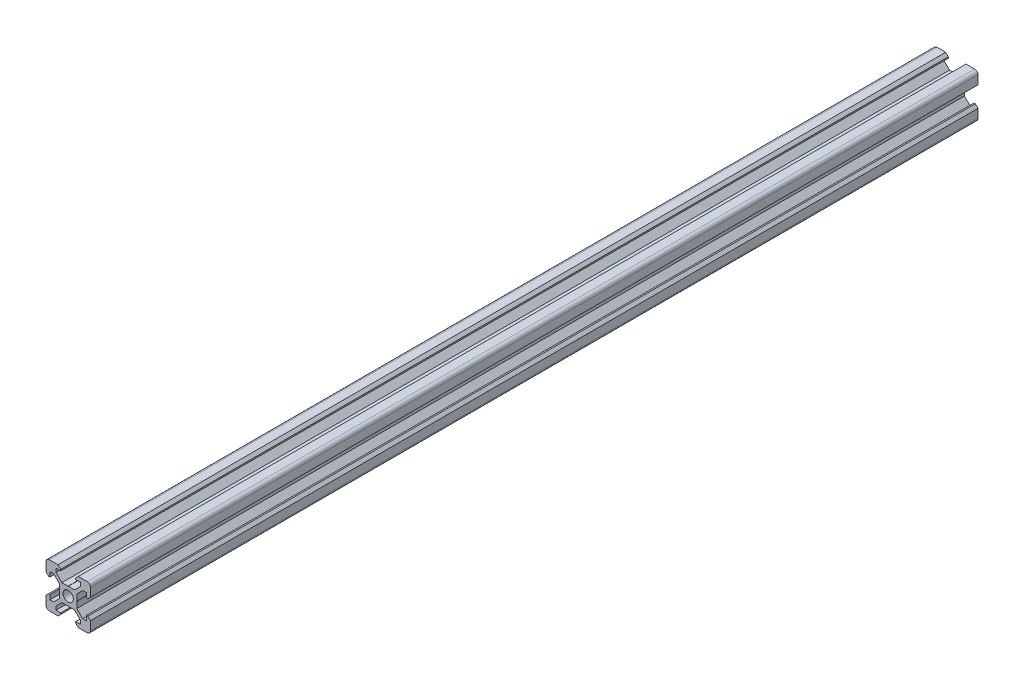
SolidWorks part; units mm, degrees
material "1060 Alloy"
ref_plane "Front Plane" through (0, 0, 0) normal (0, 0, 1) x (1, 0, 0)
ref_plane "Top Plane" through (0, 0, 0) normal (0, 1, 0) x (1, 0, 0)
ref_plane "Right Plane" through (0, 0, 0) normal (1, 0, 0) x (0, 0, -1)
sketch "Sketch1" plane through (0, 0, 0) normal (0, 0, 1) x (1, 0, 0)
  line L5 (0, 0) -> (-12.7681, 12.7681) construction
  line L6 (-2.8393, 3.9) -> (-5.5, 6.5607)
  line L15 (-5.5, 6.5607) -> (-5.5, 8.2)
  line L16 (-5.5, 8.2) -> (-3.395, 8.2)
  line L20 (-3.395, 8.2) -> (-3.395, 8.815)
  line L21 (-3.395, 8.815) -> (-4.58, 10)
  line L22 (-4.58, 10) -> (-10, 10)
  line L23 (-10, 4.58) -> (-10, 10)
  line L24 (-8.815, 3.395) -> (-10, 4.58)
  line L25 (-8.2, 3.395) -> (-8.815, 3.395)
  line L26 (-8.2, 5.5) -> (-8.2, 3.395)
  line L27 (-6.5607, 5.5) -> (-8.2, 5.5)
  line L28 (-3.9, 2.8393) -> (-6.5607, 5.5)
  line L41 (0, 0) -> (0, 15.9187) construction
  line L54 (-2.8393, 3.9) -> (0, 3.9)
  line L67 (0, 0) -> (-13.9599, 0) construction
  line L72 (-3.9, 2.8393) -> (-3.9, 0)
  line L73 (3.9, 2.8393) -> (6.5607, 5.5)
  line L74 (6.5607, 5.5) -> (8.2, 5.5)
  line L75 (8.2, 5.5) -> (8.2, 3.395)
  line L76 (8.2, 3.395) -> (8.815, 3.395)
  line L77 (8.815, 3.395) -> (10, 4.58)
  line L78 (10, 4.58) -> (10, 10)
  line L79 (4.58, 10) -> (10, 10)
  line L80 (3.395, 8.815) -> (4.58, 10)
  line L81 (3.395, 8.2) -> (3.395, 8.815)
  line L82 (5.5, 8.2) -> (3.395, 8.2)
  line L83 (5.5, 6.5607) -> (5.5, 8.2)
  line L84 (2.8393, 3.9) -> (5.5, 6.5607)
  line L85 (3.9, 2.8393) -> (3.9, 0)
  line L86 (2.8393, 3.9) -> (0, 3.9)
  line L87 (2.8393, -3.9) -> (5.5, -6.5607)
  line L88 (5.5, -6.5607) -> (5.5, -8.2)
  line L89 (5.5, -8.2) -> (3.395, -8.2)
  line L90 (3.395, -8.2) -> (3.395, -8.815)
  line L91 (3.395, -8.815) -> (4.58, -10)
  line L92 (4.58, -10) -> (10, -10)
  line L93 (10, -4.58) -> (10, -10)
  line L94 (8.815, -3.395) -> (10, -4.58)
  line L95 (8.2, -3.395) -> (8.815, -3.395)
  line L96 (8.2, -5.5) -> (8.2, -3.395)
  line L97 (6.5607, -5.5) -> (8.2, -5.5)
  line L98 (3.9, -2.8393) -> (6.5607, -5.5)
  line L99 (2.8393, -3.9) -> (0, -3.9)
  line L100 (3.9, -2.8393) -> (3.9, 0)
  line L101 (-3.9, -2.8393) -> (-6.5607, -5.5)
  line L102 (-6.5607, -5.5) -> (-8.2, -5.5)
  line L103 (-8.2, -5.5) -> (-8.2, -3.395)
  line L104 (-8.2, -3.395) -> (-8.815, -3.395)
  line L105 (-8.815, -3.395) -> (-10, -4.58)
  line L106 (-10, -4.58) -> (-10, -10)
  line L107 (-4.58, -10) -> (-10, -10)
  line L108 (-3.395, -8.815) -> (-4.58, -10)
  line L109 (-3.395, -8.2) -> (-3.395, -8.815)
  line L110 (-5.5, -8.2) -> (-3.395, -8.2)
  line L111 (-5.5, -6.5607) -> (-5.5, -8.2)
  line L112 (-2.8393, -3.9) -> (-5.5, -6.5607)
  line L113 (-3.9, -2.8393) -> (-3.9, 0)
  line L114 (-2.8393, -3.9) -> (0, -3.9)
  circle A1 centre (0, 0) radius 2.3
  point P61 (0, 0)
  point P69 (0, 0)
  dimension "D1" = 45
  dimension "D2" = 1.5
  dimension "D10" = 4.6
  dimension "D3" = 6.79
  dimension "D4" = 45
  dimension "D6" = 11
  dimension "D5" = 1.8
  dimension "D7" = 9.16
  dimension "D8" = 10
  dimension "D9" = 4.3
extrude "Boss-Extrude1" add sketch "Sketch1" along normal mid plane 400
sketch "Sketch2" plane through (0, 0, 200) normal (0, 0, 1) x (1, 0, 0)
  line L0 (0, 4.0534) -> (0, 3.7466) construction
  line L1 (-0.019, 3.8049) -> (-0.05, 3.9)
  line L2 (2.8393, 3.9) -> (-2.8393, 3.9) construction
  line L3 (-0.05, 3.9) -> (0.05, 3.9)
  line L4 (0.019, 3.8049) -> (0.05, 3.9)
  arc A0 (0.019, 3.8049) -> (-0.019, 3.8049) centre (0, 3.8111) cw
  point P9 (0, 3.9)
  dimension "D2" = 0.02
  dimension "D1" = 0.1
extrude "Cut-Extrude1" cut sketch "Sketch2" against normal up to surface (400 mm away) up to face at (0, 0, -200)
pattern_circular "CirPattern1" count 4 over 360 about axis through (0, 0, 0) along (0, 0, 1) of "Cut-Extrude1"
fillet "Fillet1" radius 1.5 4 edges at (-10, -10, 0) (10, -10, 0) (-10, 10, 0) (10, 10, 0)
move or copy body "Body-Move/Copy1" [suppressed] parameters "D1"=20, "D2"=0, "D3"=0
combine bodies "Combine1" [suppressed] bodies to combine 106 103
sketch "Sketch5" [suppressed] plane through (0, 0, 325) normal (0, 0, 1) x (1, 0, 0)
  line L0 (3.9, -2.8393) -> (3.9, 2.8393)
  line L1 (3.9, 2.8393) -> (6.5607, 5.5)
  line L2 (6.5607, 5.5) -> (13.4393, 5.5)
  line L3 (13.4393, 5.5) -> (16.1, 2.8393)
  line L4 (16.1, 2.8393) -> (16.1, -2.8393)
  line L5 (16.1, -0.05) -> (16.1, -2.8393) construction
  line L6 (16.1, -2.8393) -> (13.4393, -5.5) construction
  line L7 (16.1, -2.8393) -> (13.4393, -5.5)
  line L8 (13.4393, -5.5) -> (6.5607, -5.5)
  line L9 (6.5607, -5.5) -> (3.9, -2.8393)
extrude "Cut-Extrude4" [suppressed] cut sketch "Sketch5" against normal through all
fillet "Fillet2" [suppressed] radius 1.5
move or copy body "Body-Move/Copy2" [suppressed] parameters "D1"=10, "D2"=0, "D3"=0
sketch "Sketch6" [suppressed] plane through (10, 0, 0) normal (1, 0, 0) x (0, 0, -1)
  line L0 (-40, 10) -> (-20, 10) construction
  line L1 (-40, 10) -> (40, 10) construction
  line L2 (-30, 10) -> (-30, 0) construction
  line L3 (-30, 0) -> (0, 0) construction
  circle A0 centre (-30, 0) radius 2.5
  dimension "D1" = 10
  dimension "D2" = 5
  dimension "D3" = 10
extrude "Cut-Extrude5" [suppressed] cut sketch "Sketch6" against normal through all
sketch "Sketch7" [suppressed] plane through (10, 0, 0) normal (1, 0, 0) x (0, 0, -1)
  line L0 (0, 0) -> (0, 10) construction
  line L1 (-60, 10) -> (60, 10) construction
  line L2 (0, 10) -> (-10, 10) construction
  line L3 (-10, 10) -> (-10, 0) construction
  circle A0 centre (-10, 0) radius 2.5
  circle A1 centre (10, 0) radius 2.5
  dimension "D3" = 5
  dimension "D1" = 10
  dimension "D2" = 10
extrude "Cut-Extrude6" [suppressed] cut sketch "Sketch7" against normal through all
sketch "Sketch8" [suppressed] plane through (10, 0, 0) normal (1, 0, 0) x (0, 0, -1)
  line L0 (-140, 10) -> (-140, 0) construction
  line L1 (-140, 0) -> (-70, 0) construction
  line L3 (0, 0) -> (0, 39.0643) construction
  circle A0 centre (-70, 0) radius 2.5
  circle A1 centre (70, 0) radius 2.5
  dimension "D3" = 5
  dimension "D1" = 10
  dimension "D2" = 70
extrude "Cut-Extrude7" [suppressed] cut sketch "Sketch8" against normal through all
equation "\"Drill hole\"= 5"
equation "\"D3@Sketch8\"=\"Drill hole\""
equation "\"D2@Sketch6\"=\"Drill hole\""
equation "\"D3@Sketch7\"=\"Drill hole\""
